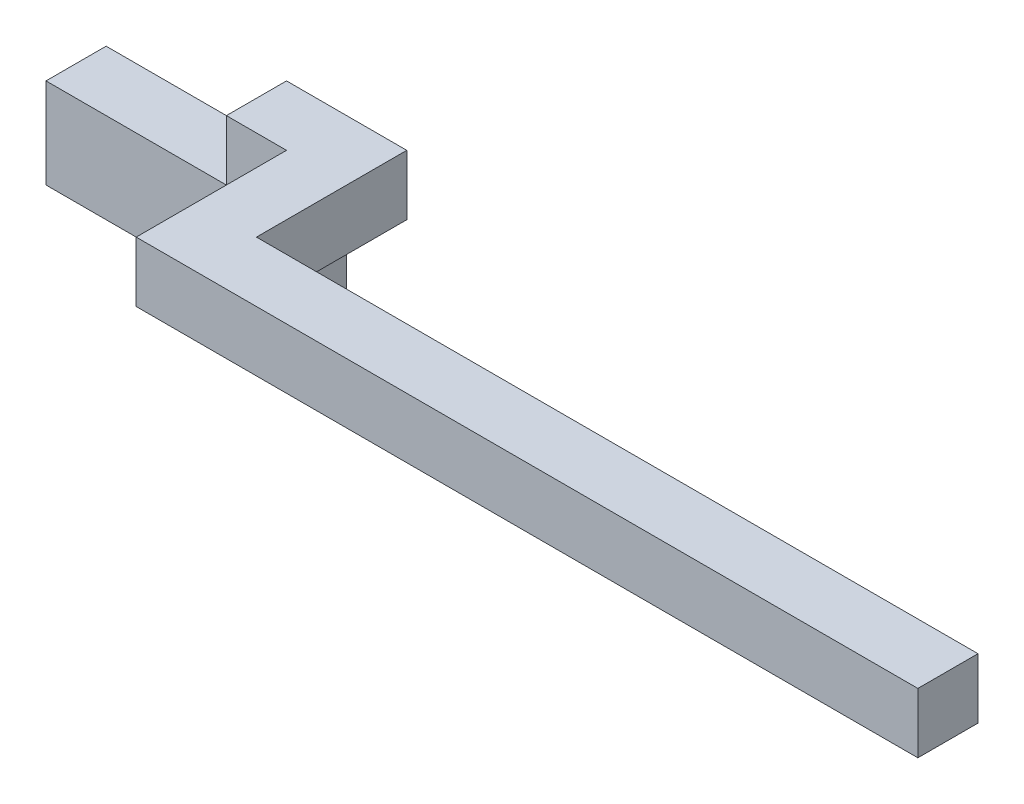
SolidWorks part; units mm, degrees
material "1060 Alloy"
ref_plane "Front Plane" through (0, 0, 0) normal (0, 0, 1) x (1, 0, 0)
ref_plane "Top Plane" through (0, 0, 0) normal (0, 1, 0) x (1, 0, 0)
ref_plane "Right Plane" through (0, 0, 0) normal (1, 0, 0) x (0, 0, -1)
ref_plane "Plane1" through (0, 0, 25.4) normal (0, 0, 1) x (1, 0, 0)
sketch "Sketch1" plane through (0, 0, 25.4) normal (0, 0, 1) x (1, 0, 0)
  line L0 (330.2, 25.4) -> (-101.6, 25.4)
  line L1 (-101.6, 25.4) -> (-101.6, -38.1)
  line L2 (-101.6, -38.1) -> (330.2, -38.1)
  line L3 (330.2, -38.1) -> (330.2, 25.4)
extrude "Boss-Extrude1" add sketch "Sketch1" against normal blind 25.4
sketch "Sketch2" plane through (0, 0, 0) normal (0, 0, -1) x (-1, 0, 0)
  line L0 (0, -38.1) -> (0, 0)
  line L1 (0, 0) -> (-330.2, 0)
  line L2 (-330.2, 0) -> (-330.2, -38.1)
  line L3 (-330.2, -38.1) -> (0, -38.1)
extrude "Cut-Extrude1" cut sketch "Sketch2" against normal through all
sketch "Sketch3" plane through (0, 0, 25.4) normal (0, 0, 1) x (1, 0, 0)
  line L0 (330.2, 0) -> (0, 0)
  line L1 (0, 0) -> (0, 25.4)
  line L2 (0, 25.4) -> (330.2, 25.4)
  line L3 (330.2, 25.4) -> (330.2, 0)
extrude "Boss-Extrude2" add sketch "Sketch3" along normal blind 63.5
sketch "Sketch4" plane through (0, 0, 25.4) normal (0, 0, 1) x (1, 0, 0)
  line L0 (-101.6, 0) -> (-25.4, 0)
  line L1 (-25.4, 0) -> (-25.4, 25.4)
  line L2 (-25.4, 25.4) -> (-101.6, 25.4)
  line L3 (-101.6, 25.4) -> (-101.6, 0)
extrude "Cut-Extrude2" cut sketch "Sketch4" against normal through all
sketch "Sketch5" plane through (0, 25.4, 0) normal (0, 1, 0) x (-1, 0, 0)
  line L0 (-25.4, 0) -> (-25.4, 63.5)
  line L1 (-25.4, 63.5) -> (-330.2, 63.5)
  line L2 (-330.2, 63.5) -> (-330.2, 0)
  line L3 (-330.2, 0) -> (-25.4, 0)
extrude "Cut-Extrude3" cut sketch "Sketch5" against normal through all
hole_wizard "Hole1" positions "Sketch7" profile "Sketch6" legacy
sketch "Sketch7" plane through (0, 0, 0) normal (0, 0, -1) x (-1, 0, 0)
  point P0 (-12.7, 12.7)
sketch "Sketch6" plane through (12.7, 12.7, 0) normal (1, 0, 0) x (0, 1, 0)
  line L0 (0, 0) -> (0, 5.08)
  line L1 (0, 5.08) -> (6.35, 5.08)
  line L2 (6.35, 5.08) -> (6.35, 0)
  line L3 (6.35, 0) -> (0, 0)
  line L4 (0, 110) -> (0, -10) construction
  dimension "Diameter" = 12.7
  dimension "Depth" = 5.08
